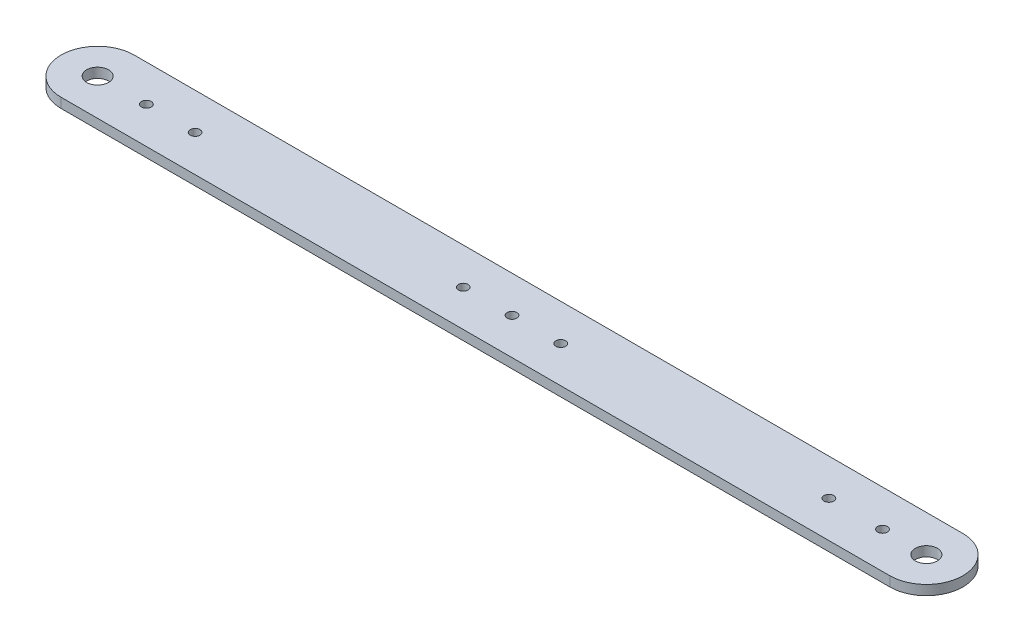
SolidWorks part; units mm, degrees
ref_plane "Front Plane" through (0, 0, 0) normal (0, 0, 1) x (1, 0, 0)
ref_plane "Top Plane" through (0, 0, 0) normal (0, 1, 0) x (1, 0, 0)
ref_plane "Right Plane" through (0, 0, 0) normal (1, 0, 0) x (0, 0, -1)
sketch "Sketch1" plane through (0, 0, 0) normal (0, 1, 0) x (1, 0, 0)
  line L0 (0, 0) -> (-170, 0) construction
  line L1 (0, 0) -> (170, 0) construction
  line L2 (-170, 15) -> (170, 15)
  line L3 (170, -15) -> (-170, -15)
  line L4 (0, 0) -> (0, 41.4571) construction
  circle A0 centre (-170, 0) radius 4.5
  circle A1 centre (170, 0) radius 4.5
  arc A2 (170, 15) -> (170, -15) centre (170, 0) cw
  arc A3 (-170, -15) -> (-170, 15) centre (-170, 0) cw
  circle A4 centre (-150, 0) radius 2
  circle A5 centre (152, 0) radius 2
  circle A6 centre (0, 0) radius 2
  circle A7 centre (-130, 0) radius 2
  circle A8 centre (-20, 0) radius 2
  circle A9 centre (20, 0) radius 2
  circle A10 centre (130, 0) radius 2
  dimension "D3" = 9
  dimension "D4" = 15
  dimension "D5" = 4
  dimension "D6" = 150
  dimension "D7" = 20
  dimension "D1" = 170
  dimension "D2" = 170
  dimension "D8" = 20
extrude "Boss-Extrude1" add sketch "Sketch1" along normal blind 4
